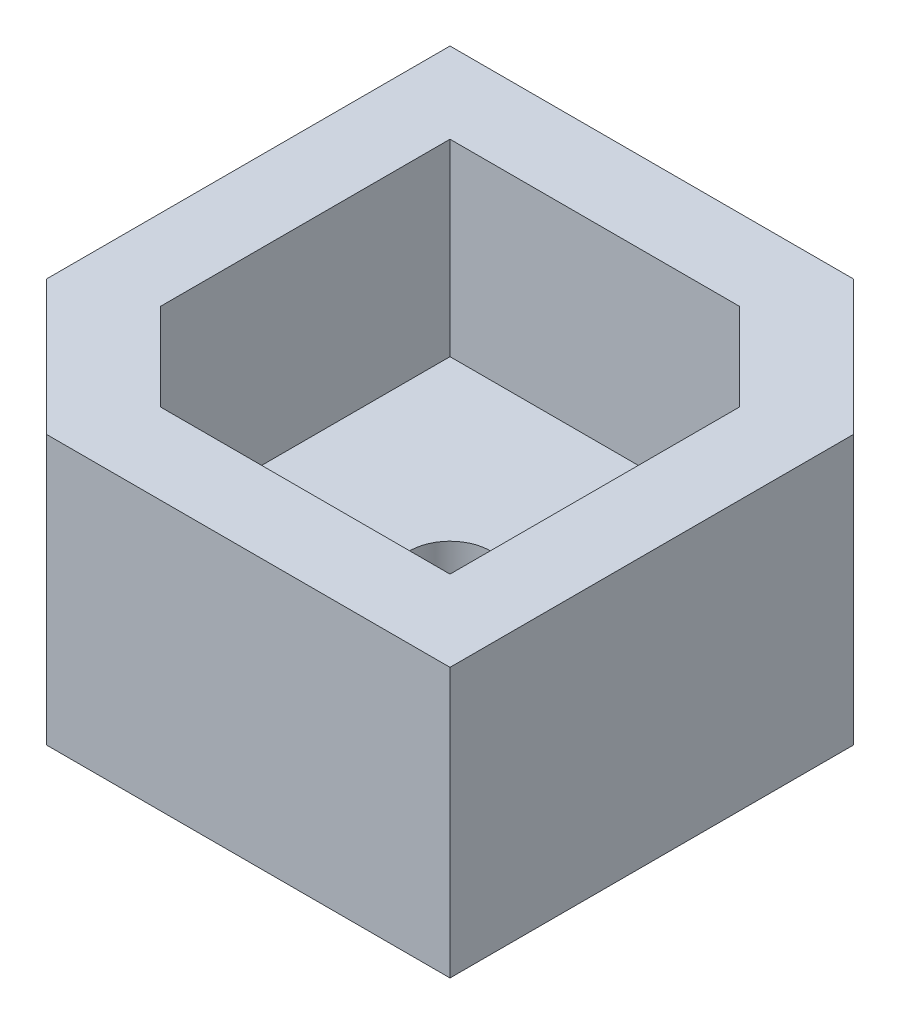
SolidWorks part; units mm, degrees
material "聚脂树脂"
ref_plane "前视基准面" through (0, 0, 0) normal (0, 0, 1) x (1, 0, 0)
ref_plane "上视基准面" through (0, 0, 0) normal (0, 1, 0) x (1, 0, 0)
ref_plane "右视基准面" through (0, 0, 0) normal (1, 0, 0) x (0, 0, -1)
other "Configuration Table"
sketch "草图1" plane through (0, 0, 0) normal (0, 1, 0) x (1, 0, 0)
  line L1 (-10, -10) -> (10, -10)
  line L2 (-10, -10) -> (-10, 10)
  line L3 (-10, 10) -> (10, 10)
  line L4 (10, -10) -> (10, 10)
  line L5 (-10, -10) -> (10, 10) construction
  line L6 (-10, 10) -> (10, -10) construction
  circle A0 centre (0, 0) radius 1.5
  point P0 (0, 0)
  dimension "D3" = 3
  dimension "D1" = 20
  dimension "D2" = 20
extrude "凸台-拉伸1" add sketch "草图1" along normal blind 3
chamfer "倒角1" distance 5 angle 45 2 edges at (10, 1.5, -10) (-10, 1.5, 10)
sketch "草图2" plane through (0, 3, 0) normal (0, 1, 0) x (1, 0, 0)
  line L0 (-7, 7) -> (-7, -3.7574)
  line L1 (-7, -3.7574) -> (-3.7574, -7)
  line L2 (-3.7574, -7) -> (7, -7)
  line L3 (7, -7) -> (7, 3.7574)
  line L4 (7, 3.7574) -> (3.7574, 7)
  line L5 (3.7574, 7) -> (-7, 7)
  line L6 (10, -10) -> (10, 5)
  line L7 (10, 5) -> (5, 10)
  line L8 (5, 10) -> (-10, 10)
  line L9 (-10, 10) -> (-10, -5)
  line L10 (-10, -5) -> (-5, -10)
  line L11 (-5, -10) -> (10, -10)
  line L12 (10, -10) -> (10, 5)
  line L13 (10, 5) -> (5, 10)
  line L14 (5, 10) -> (-10, 10)
  line L15 (-10, 10) -> (-10, -5)
  line L16 (-10, -5) -> (-5, -10)
  line L17 (-5, -10) -> (10, -10)
  dimension "D1" = 0
  dimension "D2" = 3
extrude "凸台-拉伸2" add sketch "草图2" along normal blind 7
